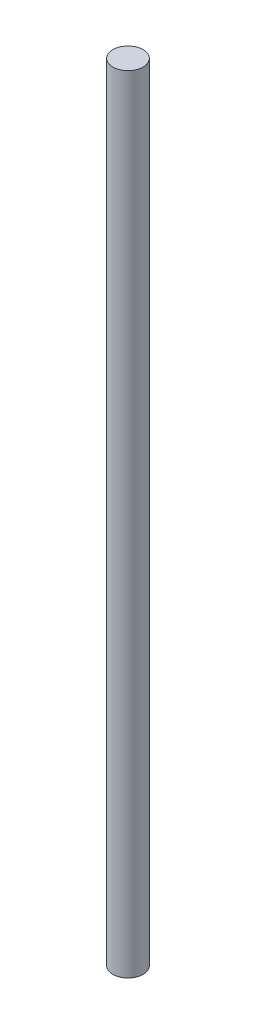
SolidWorks part; units mm, degrees
ref_plane "Front Plane" through (0, 0, 0) normal (0, 0, 1) x (1, 0, 0)
ref_plane "Top Plane" through (0, 0, 0) normal (0, 1, 0) x (1, 0, 0)
ref_plane "Right Plane" through (0, 0, 0) normal (1, 0, 0) x (0, 0, -1)
sketch "Sketch1" plane through (0, 0, 0) normal (0, 1, 0) x (1, 0, 0)
  circle A0 centre (0, 0) radius 3.175
  dimension "D1" = 6.35
extrude "Boss-Extrude1" add sketch "Sketch1" along normal blind 165
